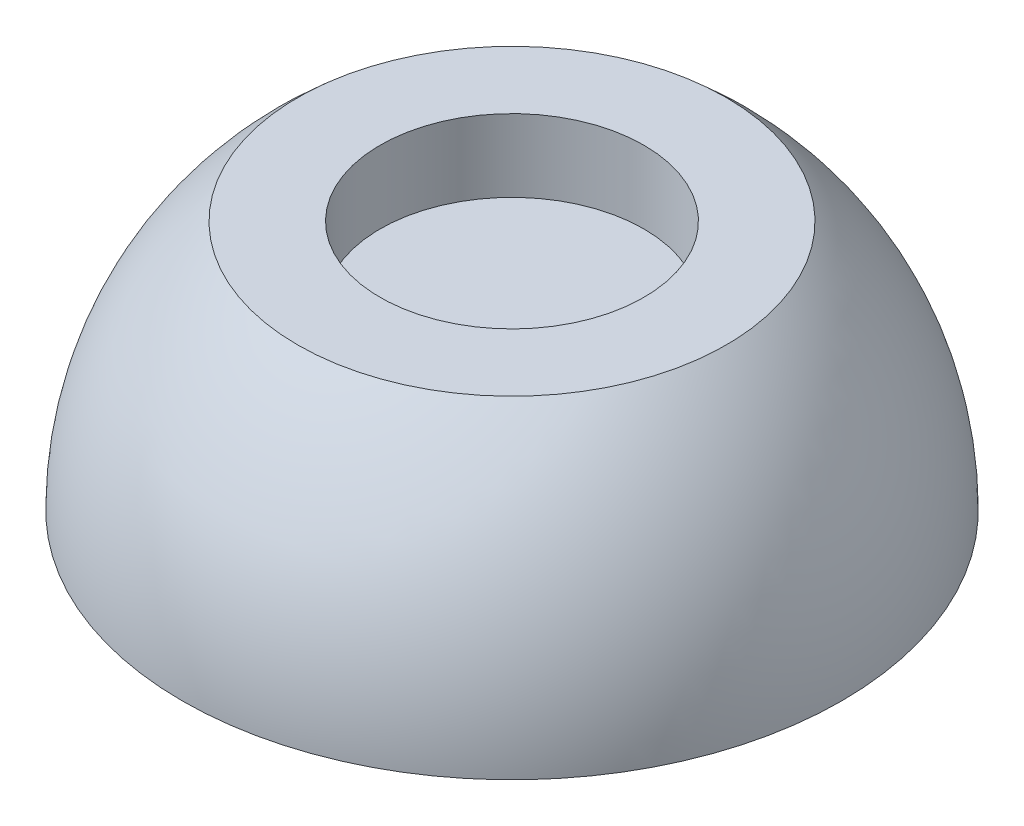
SolidWorks part; units mm, degrees
ref_plane "Front Plane" through (0, 0, 0) normal (0, 0, 1) x (1, 0, 0)
ref_plane "Top Plane" through (0, 0, 0) normal (0, 1, 0) x (1, 0, 0)
ref_plane "Right Plane" through (0, 0, 0) normal (1, 0, 0) x (0, 0, -1)
sketch "Sketch1" plane through (0, 0, 0) normal (0, 0, 1) x (1, 0, 0)
  line L0 (12.5, 0) -> (0, 0)
  line L1 (0, 0) -> (0, 12.5) construction
  line L2 (0, 0) -> (0, 6.75)
  line L3 (0, 6.75) -> (5, 6.75)
  line L4 (5, 6.75) -> (5, 9.5)
  line L5 (5, 9.5) -> (8.124, 9.5)
  arc A0 (0, 12.5) -> (12.5, 0) centre (0, 0) cw construction
  arc A1 (12.5, 0) -> (8.124, 9.5) centre (0, 0) ccw
  dimension "D1" = 12.5
  dimension "D2" = 3
  dimension "D3" = 10
  dimension "D4" = 2.75
revolve "Revolve1" add sketch "Sketch1" angle 360 about L1
sketch "Sketch2" plane through (0, 0, 0) normal (0, 1, 0) x (1, 0, 0)
  line L0 (0, 9) -> (0, 0) construction
  line L1 (0, 9) -> (-8.5595, 2.7812) construction
  line L2 (-8.5595, 2.7812) -> (-5.2901, -7.2812) construction
  line L3 (-5.2901, -7.2812) -> (5.2901, -7.2812) construction
  line L4 (5.2901, -7.2812) -> (8.5595, 2.7812) construction
  line L5 (8.5595, 2.7812) -> (0, 9) construction
  line L6 (0, 9) -> (2.5562, 3.5183)
  line L7 (2.5562, 3.5183) -> (8.5595, 2.7812)
  line L8 (8.5595, 2.7812) -> (4.136, -1.3439)
  line L9 (4.136, -1.3439) -> (5.2901, -7.2812)
  line L10 (5.2901, -7.2812) -> (0, -4.3488)
  line L11 (0, -4.3488) -> (-5.2901, -7.2812)
  line L12 (-5.2901, -7.2812) -> (-4.136, -1.3439)
  line L13 (-4.136, -1.3439) -> (-8.5595, 2.7812)
  line L14 (-8.5595, 2.7812) -> (-2.5562, 3.5183)
  line L15 (-2.5562, 3.5183) -> (0, 9)
  circle A0 centre (0, 0) radius 7.2812 construction
  dimension "D1" = 50
  dimension "D2" = 9
extrude "Cut-Extrude1" cut sketch "Sketch2" along normal blind 5
